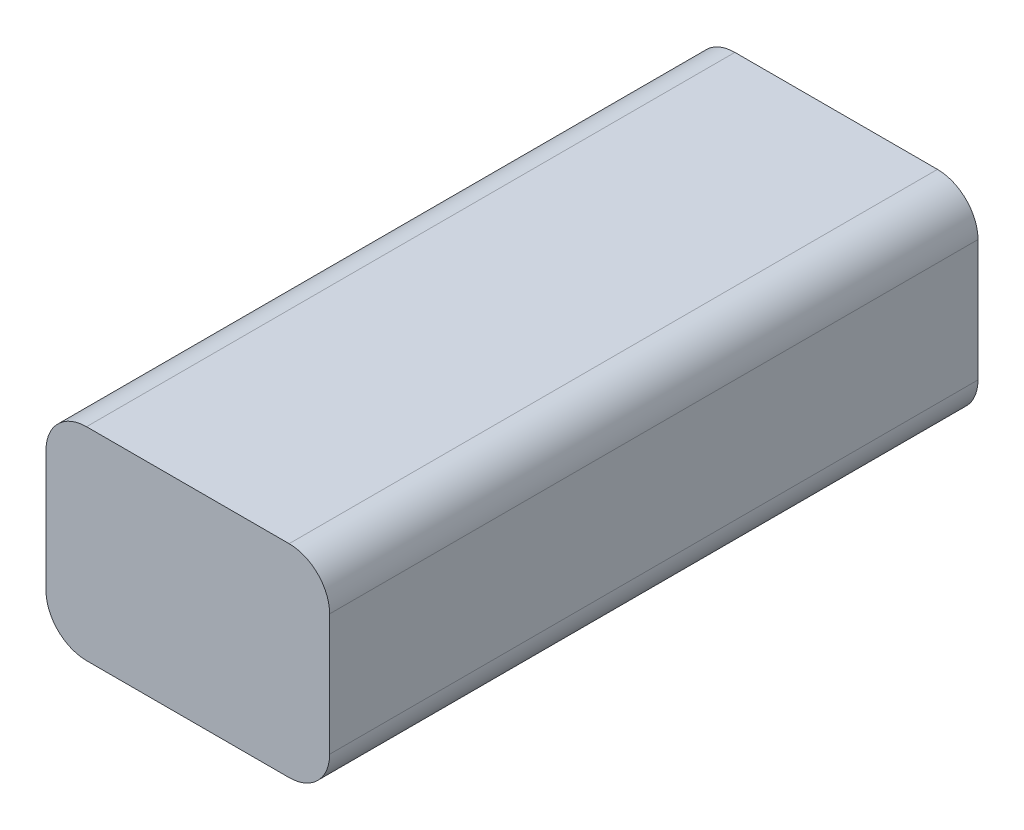
SolidWorks part; units mm, degrees
ref_plane "Front Plane" through (0, 0, 0) normal (0, 0, 1) x (1, 0, 0)
ref_plane "Top Plane" through (0, 0, 0) normal (0, 1, 0) x (1, 0, 0)
ref_plane "Right Plane" through (0, 0, 0) normal (1, 0, 0) x (0, 0, -1)
sketch "Sketch1" plane through (0, 0, 0) normal (0, 0, 1) x (1, 0, 0)
  line L1 (-25, 25) -> (25, 25)
  line L2 (-35, 15) -> (-35, -15)
  line L3 (-25, -25) -> (25, -25)
  line L4 (35, 15) -> (35, -15)
  arc A0 (-35, -15) -> (-25, -25) centre (-25, -15) ccw
  arc A1 (25, -25) -> (35, -15) centre (25, -15) ccw
  arc A2 (25, 25) -> (35, 15) centre (25, 15) cw
  arc A3 (-25, 25) -> (-35, 15) centre (-25, 15) ccw
  point P4 (-35, 0)
  point P5 (0, 25)
  point P7 (0, 0)
  point P10 (-35, -25)
  point P15 (35, 25)
  point P18 (-35, 25)
  dimension "D3" = 10
  dimension "D1" = 70
  dimension "D2" = 50
extrude "Boss-Extrude1" add sketch "Sketch1" along normal blind 160
